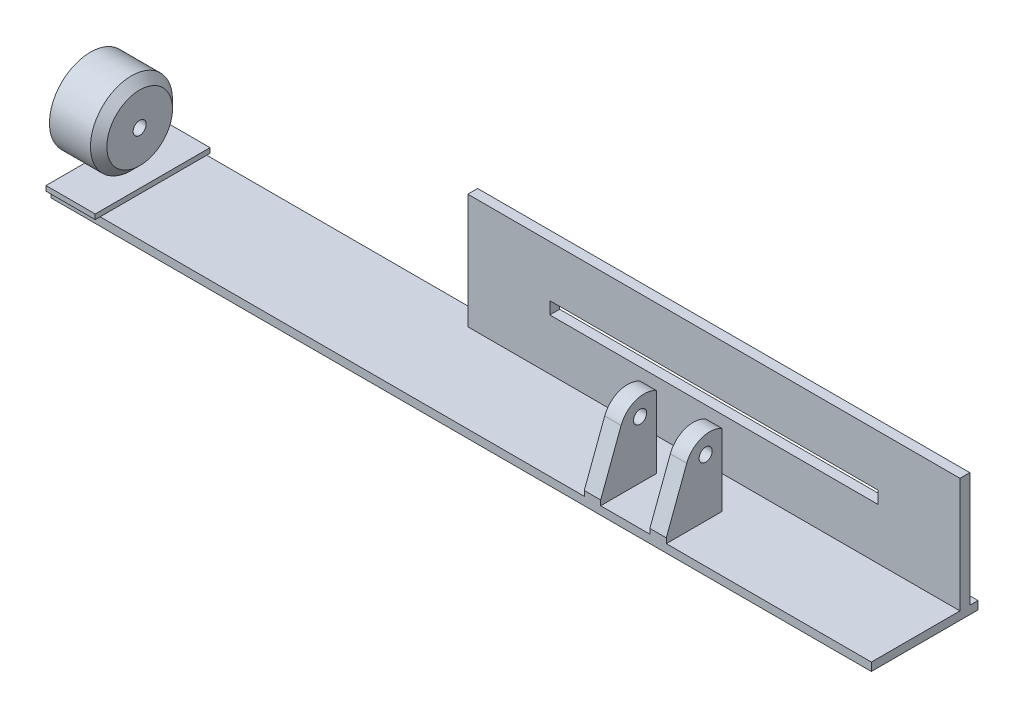
SolidWorks part; units mm, degrees
ref_plane "Front Plane" through (0, 0, 0) normal (0, 0, 1) x (1, 0, 0)
ref_plane "Top Plane" through (0, 0, 0) normal (0, 1, 0) x (1, 0, 0)
ref_plane "Right Plane" through (0, 0, 0) normal (1, 0, 0) x (0, 0, -1)
sketch "Sketch1" plane through (0, 0, 0) normal (0, 1, 0) x (1, 0, 0)
  line L1 (-250, -32.5) -> (250, -32.5)
  line L2 (-250, -32.5) -> (-250, 32.5)
  line L3 (-250, 32.5) -> (250, 32.5)
  line L4 (250, -32.5) -> (250, 32.5)
  line L5 (-250, -32.5) -> (250, 32.5) construction
  line L6 (-250, 32.5) -> (250, -32.5) construction
  point P0 (0, 0)
  dimension "D1" = 500
  dimension "D2" = 65
extrude "Boss-Extrude1" add sketch "Sketch1" along normal blind 5
sketch "Sketch2" plane through (0, 5, 0) normal (0, 1, 0) x (1, 0, 0)
  line L0 (250, 27.5) -> (-50, 27.5)
  line L1 (250, -32.5) -> (250, 32.5) construction
  line L2 (-50, 27.5) -> (-50, 21.5)
  line L3 (-50, 21.5) -> (250, 21.5)
  line L4 (250, 21.5) -> (250, 27.5)
  dimension "D1" = 300
  dimension "D2" = 6
  dimension "D3" = 5
extrude "Boss-Extrude2" add sketch "Sketch2" along normal blind 70
sketch "Sketch3" plane through (0, 0, -21.5) normal (0, 0, 1) x (1, 0, 0)
  line L0 (250, 40) -> (-50, 40) construction
  line L1 (250, 75) -> (250, 5) construction
  line L2 (-50, 75) -> (-50, 5) construction
  line L3 (100, 40) -> (100, 86.8674) construction
  line L4 (0, 40) -> (0, 36.235)
  line L5 (0, 43.765) -> (200, 43.765)
  line L6 (200, 43.765) -> (200, 40)
  line L7 (200, 40) -> (200, 36.235)
  line L8 (200, 36.235) -> (0, 36.235)
  line L9 (0, 43.765) -> (0, 40)
  point P13 (100, 43.765)
  point P17 (100, 36.235)
  dimension "D1" = 100
  dimension "D2" = 7.53
extrude "Cut-Extrude1" cut sketch "Sketch3" against normal through all
sketch "Sketch4" plane through (0, 5, 0) normal (0, 1, 0) x (1, 0, 0)
  line L0 (100, 21.5) -> (100, -59.0898) construction
  line L1 (-50, 21.5) -> (250, 21.5) construction
ref_plane "Plane1" through (115, 0, 0) normal (1, 0, 0) x (0, 0, -1)
sketch "Sketch7" plane through (250, 0, 0) normal (1, 0, 0) x (0, 0, -1)
  line L0 (-32.5, 5) -> (-32.5, 8.0604)
  line L1 (-32.5, 8.0604) -> (-20.0468, 41.1691)
  line L2 (1.5, 48.821) -> (1.5, 5)
  line L3 (-32.5, 5) -> (21.5, 5) construction
  line L4 (1.5, 5) -> (-32.5, 5)
  line L5 (21.5, 75) -> (21.5, 5) construction
  arc A0 (-20.0468, 41.1691) -> (1.5, 48.821) centre (-6.0444, 35.9024) cw
  point P6 (-11.0508, 50)
  dimension "D1" = 45
  dimension "D2" = 20
sketch "Sketch8" plane through (115, 0, 0) normal (1, 0, 0) x (0, 0, -1)
  line L0 (-32.5, 5) -> (-32.5, 8.0604) construction
  line L1 (1.5, 5) -> (-32.5, 5) construction
  line L2 (1.5, 48.821) -> (1.5, 5) construction
  line L3 (-32.5, 8.0604) -> (-20.0468, 41.1691) construction
  line L4 (-32.5, 5) -> (-32.5, 8.0604)
  line L5 (1.5, 5) -> (-32.5, 5)
  line L6 (1.5, 48.821) -> (1.5, 5)
  line L7 (-32.5, 8.0604) -> (-20.0468, 41.1691)
  arc A0 (1.5, 48.821) -> (-20.0468, 41.1691) centre (-6.0444, 35.9024) ccw construction
  arc A1 (1.5, 48.821) -> (-20.0468, 41.1691) centre (-6.0444, 35.9024) ccw
extrude "Boss-Extrude4" add sketch "Sketch8" along normal blind 10
ref_plane "Plane2" through (100, 0, 0) normal (1, 0, 0) x (0, 0, -1)
mirror "Mirror1" about plane through (100, 0, 0) normal (1, 0, 0) of "Boss-Extrude4"
sketch "Sketch9" plane through (125, 0, 0) normal (1, 0, 0) x (0, 0, -1)
  line L0 (-32.5, 5) -> (1.5, 5) construction
  line L1 (1.5, 5) -> (1.5, 48.821) construction
  circle A0 centre (-8.5, 40) radius 4
  dimension "D1" = 35
  dimension "D3" = 8
  dimension "D2" = 10
extrude "Cut-Extrude2" cut sketch "Sketch9" against normal through all
sketch "Sketch10" plane through (0, 5, 0) normal (0, 1, 0) x (1, 0, 0)
  line L0 (-250.0943, -35.5) -> (-250.0943, 34.5)
  line L2 (-250.0943, 34.5) -> (-220.0943, 34.5)
  line L4 (-220.0943, 34.5) -> (-220.0943, -35.5)
  line L5 (-220.0943, -35.5) -> (-250.0943, -35.5)
  line L6 (-250, -32.5) -> (75, -32.5) construction
  dimension "D1" = 70
  dimension "D2" = 3
  dimension "D3" = 30
extrude "Boss-Extrude5" add sketch "Sketch10" along normal blind 3
ref_plane "Plane3" through (-250, 0, 0) normal (1, 0, 0) x (0, 0, -1)
sketch "Sketch11" plane through (-250, 0, 0) normal (1, 0, 0) x (0, 0, -1)
  circle A0 centre (-8.5, 40) radius 25
  point P0 (-8.5, 40)
  dimension "D1" = 50
extrude "Boss-Extrude6" add sketch "Sketch11" along normal blind 30 separate body
chamfer "Chamfer1" distance 5 angle 45 1 edges at (-220, 40, -16.5)
sketch "Sketch12" plane through (-220, 0, 0) normal (1, 0, 0) x (0, 0, -1)
  circle A0 centre (-8.5, 40) radius 4
extrude "Cut-Extrude3" cut sketch "Sketch12" against normal blind 10
